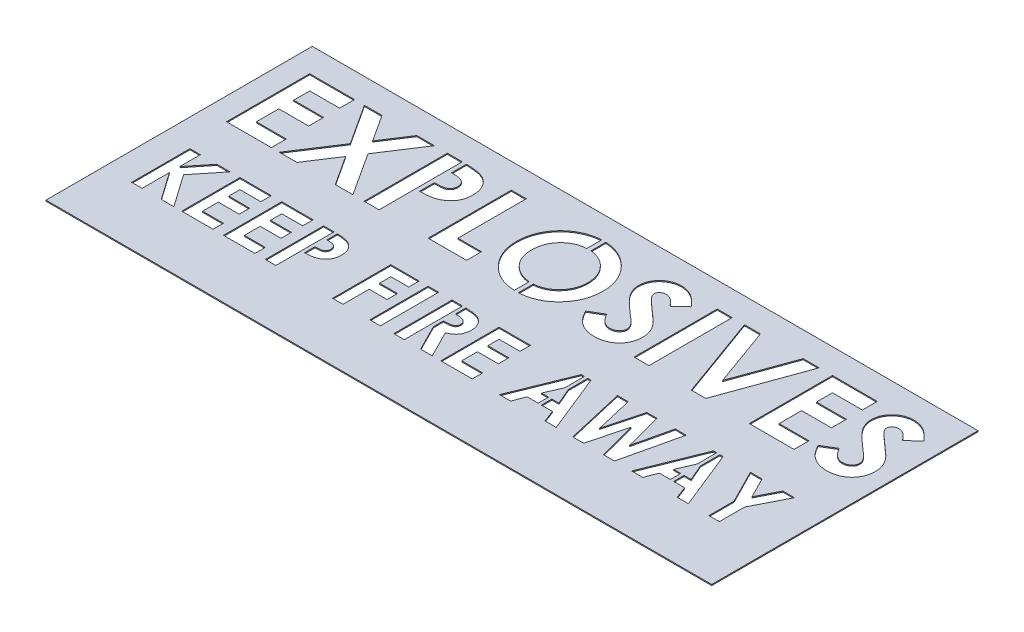
SolidWorks part; units mm, degrees
ref_plane "Front Plane" through (0, 0, 0) normal (0, 0, 1) x (1, 0, 0)
ref_plane "Top Plane" through (0, 0, 0) normal (0, 1, 0) x (1, 0, 0)
ref_plane "Right Plane" through (0, 0, 0) normal (1, 0, 0) x (0, 0, -1)
sketch "Sketch1" plane through (0, 0, 0) normal (0, 1, 0) x (1, 0, 0)
  line L1 (127, -50.8) -> (-127, -50.8)
  line L2 (127, -50.8) -> (127, 50.8)
  line L3 (127, 50.8) -> (-127, 50.8)
  line L4 (-127, -50.8) -> (-127, 50.8)
  line L5 (127, -50.8) -> (-127, 50.8) construction
  line L6 (127, 50.8) -> (-127, -50.8) construction
  point P0 (0, 0)
  dimension "D1" = 254
  dimension "D2" = 101.6
extrude "Boss-Extrude1" add sketch "Sketch1" along normal blind 0.4
sketch "Sketch2" plane through (0, 0.4, 0) normal (0, 1, 0) x (1, 0, 0)
  line L0 (-127, 9.525) -> (127, 9.525) construction
  line L1 (-127, 50.8) -> (-127, -50.8) construction
  line L2 (127, -50.8) -> (127, 50.8) construction
  line L3 (0, 0) -> (127, 0) construction
  line L4 (-127, -28.575) -> (127, -28.575) construction
  text T0 "<b>EXPLOSIVES</b>" font "Century Gothic" height 31.75
  text T1 "<b>KEEP FIRE AWAY</b>" font "Century Gothic" height 22.225
  dimension "D1" = 9.525
  dimension "D2" = 28.575
extrude "Cut-Extrude1" cut sketch "Sketch2" against normal through all
sketch "Sketch3" plane through (0, 0.4, 0) normal (0, 1, 0) x (1, 0, 0)
  line L0 (-65.9423, 41.275) -> (-59.5821, 41.275) construction
  line L1 (34.6175, -24.016) -> (33.9825, -24.016) construction
  line L2 (-60.2436, 41.275) -> (-59.5821, 41.275) construction
  line L3 (-60.2436, 23.3647) -> (-60.2436, 41.275)
  line L4 (-58.6561, 41.2679) -> (-58.6561, 23.38)
  line L5 (-7.1488, 36.3904) -> (-7.0598, 42.0891) construction
  line L6 (-7.854, 42.0721) -> (-7.854, 8.7339)
  line L7 (-6.2665, 8.7336) -> (-6.2665, 42.0473)
  line L8 (-6.2665, 42.0473) -> (-6.2665, 42.0649)
  line L9 (-65.5353, -6.35) -> (-61.0831, -6.35) construction
  line L10 (-61.5462, -6.35) -> (-61.0831, -6.35) construction
  line L11 (-61.5462, -18.8872) -> (-61.5462, -6.35)
  line L12 (-60.2762, -6.3576) -> (-60.2762, -18.8724)
  line L13 (-12.5372, -18.8872) -> (-12.5372, -6.35)
  line L14 (-16.5263, -6.35) -> (-11.8783, -6.35) construction
  line L15 (33.9825, -6.35) -> (35.2525, -6.35) construction
  line L16 (-11.1837, -18.8872) -> (-12.5372, -18.8872) construction
  line L17 (39.4592, -24.016) -> (29.7847, -24.016) construction
  line L18 (-12.5372, -6.35) -> (-11.8783, -6.35) construction
  line L19 (-11.2672, -18.8872) -> (-12.5372, -18.8872) construction
  line L20 (-11.2672, -6.3538) -> (-11.2672, -18.8872)
  line L21 (32.7632, -6.35) -> (36.4718, -6.35) construction
  line L22 (35.2525, -24.016) -> (34.6175, -24.016) construction
  line L23 (32.7632, -6.35) -> (36.4718, -6.35) construction
  line L24 (34.6175, -24.016) -> (34.6175, -6.35) construction
  line L25 (33.9825, -6.35) -> (33.9825, -24.016)
  line L26 (35.2525, -24.016) -> (35.2525, -6.35)
  line L27 (83.1968, -6.35) -> (86.9054, -6.35) construction
  line L28 (89.8928, -24.016) -> (80.2184, -24.016) construction
  line L29 (83.1968, -6.35) -> (86.9054, -6.35) construction
  line L30 (89.8928, -24.016) -> (80.2184, -24.016) construction
  line L31 (85.0556, -24.016) -> (85.0511, -6.35) construction
  line L32 (84.4206, -6.35) -> (84.4206, -24.016)
  line L33 (85.6906, -24.0157) -> (85.6906, -6.35)
  line L34 (84.4206, -24.016) -> (85.6906, -24.0157) construction
  line L35 (85.6906, -6.35) -> (84.4206, -6.35) construction
  line L36 (-60.2436, 23.3647) -> (-60.2436, 21.4896)
  line L37 (-60.2436, 23.3647) -> (-60.2436, 9.525) construction
  line L38 (-60.2436, 21.4896) -> (-58.6561, 21.4896)
  line L39 (-58.6561, 21.4896) -> (-58.6561, 23.38)
  line L40 (-60.2436, 41.275) -> (-60.2436, 42.7723)
  line L41 (-60.2436, 42.7723) -> (-58.6561, 42.7723)
  line L42 (-58.6561, 42.7723) -> (-58.6561, 41.2679)
  line L43 (-6.2665, 42.0473) -> (-6.2665, 43.225)
  line L44 (-6.2665, 43.225) -> (-7.854, 43.225)
  line L45 (-7.854, 43.225) -> (-7.854, 42.0721)
  line L46 (-6.2665, 8.7336) -> (-6.2665, 7.0601)
  line L47 (-6.2665, 7.0601) -> (-7.854, 7.0601)
  line L48 (-7.854, 7.0601) -> (-7.854, 8.7339)
  line L49 (-60.2762, -6.3576) -> (-60.2762, -5.1927)
  line L50 (-60.2762, -5.1927) -> (-61.5462, -5.1927)
  line L51 (-61.5462, -5.1927) -> (-61.5462, -6.35)
  line L52 (-60.2762, -18.8724) -> (-60.2762, -20.3856)
  line L53 (-60.2762, -20.3856) -> (-61.5462, -20.3856)
  line L54 (-61.5462, -18.8872) -> (-61.5462, -28.575) construction
  line L55 (-61.5462, -20.3856) -> (-61.5462, -18.8872)
  line L56 (-11.2672, -6.3538) -> (-11.2672, -5.3156)
  line L57 (-11.2672, -5.3156) -> (-12.5372, -5.3156)
  line L58 (-12.5372, -5.3156) -> (-12.5372, -6.35)
  line L59 (-11.2672, -18.8872) -> (-11.2672, -21.0537)
  line L60 (-11.2672, -21.0537) -> (-12.5372, -21.0537)
  line L61 (-12.5372, -18.8872) -> (-12.5372, -28.575) construction
  line L62 (-12.5372, -21.0537) -> (-12.5372, -18.8872)
  line L63 (35.2525, -6.35) -> (35.2525, -5.3156)
  line L64 (35.2525, -5.3156) -> (33.9825, -5.3156)
  line L65 (33.9825, -5.3156) -> (33.9825, -6.35)
  line L66 (35.2525, -24.016) -> (35.2525, -24.9696)
  line L67 (35.2525, -24.9696) -> (33.9825, -24.9696)
  line L68 (33.9825, -24.9696) -> (33.9825, -24.016)
  line L69 (85.6906, -6.35) -> (85.6906, -5.3156)
  line L70 (85.6906, -5.3156) -> (84.4206, -5.3156)
  line L71 (84.4206, -5.3156) -> (84.4206, -6.35)
  line L72 (85.6906, -24.0157) -> (85.6906, -25.9909)
  line L73 (85.6906, -25.9909) -> (84.4206, -25.9909)
  line L74 (84.4206, -25.9909) -> (84.4206, -24.016)
  spline S0 degree 3 poles (383.5394, -1927.5608) (-38.8451, 59.062) (-43.4399, 25.3763) (-54.8741, 23.6308) (-55.5465, 23.5489) (-56.3099, 23.4786) (-57.1649, 23.4307) (-58.1106, 23.3934) (-87.054, 22.6351) (-116.0138, 50.1547) (-120.4882, -1975.0593) knots -5.060584 -5.060584 -5.060584 -5.060584 0.077373 0.167614 0.272108 0.390016 0.521363 0.667272 0.82681 13.882944 13.882944 13.882944 13.882944 only from (-53.7753, 23.8481) to (-60.2436, 23.3647) construction
  spline S1 degree 3 poles (-112.4571, 2039.966) (-113.971, 10.9667) (-85.535, 42.2922) (-57.2087, 41.226) (-56.1421, 41.148) (-55.1653, 41.0517) (-54.2787, 40.9166) (-53.4812, 40.7617) (-52.7726, 40.5729) (-52.1449, 40.3489) (-51.5815, 40.0848) (-51.0484, 39.8036) (-50.5576, 39.4679) (-50.0843, 39.114) (-49.6556, 38.708) (-49.2447, 38.277) (-48.869, 37.8038) (-48.5269, 37.2943) (-48.2165, 36.7578) (-47.9453, 36.1934) (-47.7253, 35.6001) (-47.5407, 34.9818) (-47.3925, 34.3386) (-47.2939, 33.6664) (-45.8884, 19.0605) (-81.1777, 2.9062) (1951.7962, 86.9694) knots -4.62995 -4.62995 -4.62995 -4.62995 0.070781 0.136552 0.197012 0.252923 0.303687 0.349719 0.39124 0.428479 0.463057 0.49715 0.531002 0.564226 0.597701 0.631421 0.665597 0.700451 0.735881 0.771092 0.806975 0.843534 0.88094 0.919294 0.95918 3.378005 3.378005 3.378005 3.378005 only from (-59.5821, 41.275) to (-47.2179, 32.2563) construction
  spline S2 degree 3 poles (-58.6561, 23.38) (-58.81, 23.3763) (-59.3391, 23.366) (-59.8683, 23.3652) (-60.2436, 23.3647) knots 0.75576 0.75576 0.75576 0.75576 0.82681 1 1 1 1 construction
  spline S3 degree 3 poles (-59.5821, 41.275) (-59.2734, 41.2736) (-58.9647, 41.2722) (-58.6561, 41.2679) knots 0 0 0 0 0.052578 0.052578 0.052578 0.052578 construction
  spline S4 degree 3 poles (-90.3304, -1989.1071) (40.631, 60.3711) (13.1894, 5.52) (-10.4257, 8.9974) (-12.0345, 9.3699) (-13.5593, 9.9257) (-15.0158, 10.6206) (-16.3933, 11.4764) (-17.6912, 12.4917) (-18.9022, 13.6405) (-19.9993, 14.8976) (-20.9677, 16.2255) (-21.7846, 17.6142) (-22.4499, 19.0643) (-22.9745, 20.5669) (-23.3445, 22.131) (-26.5892, 46.207) (24.4447, 73.3551) (-2022.084, -39.3514) knots -2.530865 -2.530865 -2.530865 -2.530865 0.066749 0.131152 0.193732 0.255326 0.316388 0.378027 0.440406 0.504557 0.568658 0.630986 0.692288 0.752615 0.8132 0.874016 0.936158 3.586141 3.586141 3.586141 3.586141 only from (-7.0153, 8.7109) to (-23.609, 25.4127) construction
  spline S5 degree 3 poles (2007.8991, -39.1213) (-39.7016, 73.2922) (12.3981, 46.0644) (9.0921, 21.9673) (8.7146, 20.3876) (8.1946, 18.872) (7.5127, 17.4278) (6.6911, 16.0459) (5.7081, 14.739) (4.5996, 13.5079) (3.3792, 12.3904) (2.0866, 11.4056) (0.7278, 10.5711) (-0.6952, 9.8873) (-2.1856, 9.3567) (-3.7395, 8.9823) (-27.3121, 5.6661) (-54.205, 57.9292) (64.9599, -1989.5489) knots -2.612661 -2.612661 -2.612661 -2.612661 0.065722 0.129508 0.191722 0.253161 0.314316 0.375952 0.43862 0.502973 0.567129 0.629552 0.690477 0.751072 0.811668 0.872929 0.935501 3.55637 3.55637 3.55637 3.55637 only from (9.3622, 25.3046) to (-7.0153, 8.7109) construction
  spline S6 degree 3 poles (71.0097, 2040.0874) (-53.3082, -7.8893) (-26.8068, 45.1856) (-3.8153, 41.8114) (-2.2708, 41.4281) (-0.7852, 40.8954) (0.6378, 40.1988) (2.0032, 39.3579) (3.306, 38.3571) (4.5331, 37.2195) (5.6671, 35.9825) (6.6497, 34.6506) (7.4877, 33.2584) (8.1821, 31.8021) (8.7111, 30.2716) (9.0823, 28.6748) (12.4857, 4.9459) (-41.1897, -22.3301) (2007.4548, 101.6982) knots -2.477585 -2.477585 -2.477585 -2.477585 0.063396 0.125157 0.185649 0.245977 0.306108 0.367351 0.429902 0.49454 0.559373 0.62241 0.684357 0.745807 0.80743 0.869996 0.933928 3.555613 3.555613 3.555613 3.555613 only from (-7.0598, 42.0891) to (9.3622, 25.3046) construction
  spline S7 degree 3 poles (-2022.6948, 76.2047) (16.9362, -12.9796) (-25.5032, 8.3237) (-23.4786, 27.6407) (-23.3117, 28.7252) (-23.0649, 29.7837) (-22.765, 30.8238) (-22.3765, 31.8358) (-21.9343, 32.8305) (-21.4177, 33.7961) (-20.8432, 34.7238) (-20.2163, 35.6091) (-19.5356, 36.4414) (-18.8032, 37.2261) (-18.0165, 37.9582) (-17.1859, 38.6478) (-16.2954, 39.2768) (-15.3643, 39.8605) (-14.398, 40.3883) (-13.4004, 40.8376) (-12.3919, 41.2299) (-11.3593, 41.5396) (-10.3135, 41.7918) (-9.2433, 41.9585) (9.6876, 43.9814) (30.6648, 1.6667) (-61.6622, 2041.0656) knots -2.100804 -2.100804 -2.100804 -2.100804 0.043114 0.085683 0.127594 0.169059 0.210432 0.251811 0.293444 0.335381 0.377477 0.418688 0.459873 0.500873 0.541873 0.583212 0.624763 0.666988 0.70937 0.751103 0.792568 0.833545 0.874827 0.916018 0.957859 3.05911 3.05911 3.05911 3.05911 only from (-23.609, 25.4127) to (-7.0598, 42.0891) construction
  spline S8 degree 3 poles (-7.0153, 8.7109) (-7.295, 8.7172) (-7.5746, 8.7236) (-7.854, 8.7339) knots 0 0 0 0 0.03197 0.03197 0.03197 0.03197 construction
  spline S9 degree 3 poles (-6.2665, 8.7336) (-6.516, 8.7241) (-6.7656, 8.7175) (-7.0153, 8.7109) knots 0.971159 0.971159 0.971159 0.971159 1 1 1 1 construction
  spline S10 degree 3 poles (-7.0598, 42.0891) (-6.7953, 42.0823) (-6.5308, 42.0754) (-6.2665, 42.0649) knots 0 0 0 0 0.030378 0.030378 0.030378 0.030378 construction
  spline S11 degree 3 poles (-7.854, 42.0721) (-7.5895, 42.082) (-7.3246, 42.0856) (-7.0598, 42.0891) knots 0.969595 0.969595 0.969595 0.969595 1 1 1 1 construction
  spline S12 degree 3 poles (373.5191, -1971.5508) (-45.8503, 12.1972) (-48.8248, -17.3327) (-57.7875, -18.7009) (-58.2582, -18.7582) (-58.7926, -18.8075) (-59.3911, -18.841) (-60.053, -18.8671) (-82.7824, -19.4626) (-105.584, 4.9129) (-104.0677, -2018.0259) knots -5.699386 -5.699386 -5.699386 -5.699386 0.077373 0.167614 0.272108 0.390016 0.521363 0.667272 0.82681 15.511175 15.511175 15.511175 15.511175 only from (-57.0183, -18.5488) to (-61.5462, -18.8872) construction
  spline S13 degree 3 poles (-96.6977, 1992.9451) (-104.0472, -33.2908) (-81.6537, -5.5475) (-59.4217, -6.3843) (-58.6751, -6.4389) (-57.9914, -6.5063) (-57.3707, -6.6009) (-56.8125, -6.7093) (-56.3164, -6.8414) (-55.877, -6.9982) (-55.4827, -7.1831) (-55.1095, -7.38) (-54.766, -7.615) (-54.4347, -7.8627) (-54.1346, -8.1469) (-53.8469, -8.4486) (-53.584, -8.7798) (-53.3444, -9.1365) (-53.1272, -9.512) (-52.9373, -9.9071) (-52.7833, -10.3224) (-52.6542, -10.7552) (-52.5504, -11.2055) (-52.4813, -11.676) (-51.3792, -23.1291) (-82.6139, -35.9876) (1946.3364, 50.9106) knots -5.215064 -5.215064 -5.215064 -5.215064 0.070781 0.136552 0.197012 0.252923 0.303687 0.349719 0.39124 0.428479 0.463057 0.49715 0.531002 0.564226 0.597701 0.631421 0.665597 0.700451 0.735881 0.771092 0.806975 0.843534 0.88094 0.919294 0.95918 3.678161 3.678161 3.678161 3.678161 only from (-61.0831, -6.35) to (-52.4282, -12.6631) construction
  spline S14 degree 3 poles (-60.2762, -18.8724) (-60.4368, -18.8769) (-60.8601, -18.8863) (-61.2835, -18.8868) (-61.5462, -18.8872) knots 0.72086 0.72086 0.72086 0.72086 0.82681 1 1 1 1 construction
  spline S15 degree 3 poles (-61.0831, -6.35) (-60.8141, -6.3512) (-60.5451, -6.3524) (-60.2762, -6.3576) knots 0 0 0 0 0.065456 0.065456 0.065456 0.065456 construction
  spline S16 degree 3 poles (-38.8225, 1993.0808) (-55.6175, -34.4332) (-32.7181, -5.509) (-10.1281, -6.3863) (-9.3454, -6.4323) (-8.6308, -6.5026) (-7.9848, -6.5958) (-7.4065, -6.7056) (-6.8961, -6.8308) (-6.4492, -6.9868) (-6.0459, -7.1627) (-5.67, -7.3649) (-5.3132, -7.591) (-4.9778, -7.847) (-4.6609, -8.1284) (-4.362, -8.4354) (-4.0853, -8.7705) (-3.8325, -9.1317) (-3.602, -9.5118) (-3.3984, -9.9111) (-3.2327, -10.3299) (-3.0864, -10.7623) (-2.981, -11.2144) (-2.9077, -11.6819) (-1.7182, -22.4157) (-35.2021, -34.8541) (1995.5236, 63.7548) knots -5.160685 -5.160685 -5.160685 -5.160685 0.072889 0.140186 0.202277 0.258895 0.310483 0.357095 0.398514 0.435038 0.469251 0.502805 0.53621 0.569379 0.602801 0.636666 0.670929 0.705803 0.741189 0.776304 0.812004 0.847969 0.884522 0.921974 0.960198 3.443654 3.443654 3.443654 3.443654 only from (-11.8783, -6.35) to (-2.8494, -12.6631) construction
  spline S17 degree 3 poles (-11.8783, -6.35) (-11.6746, -6.3507) (-11.4709, -6.3514) (-11.2672, -6.3538) knots 0 0 0 0 0.048328 0.048328 0.048328 0.048328 construction
  dimension "D1" = 1.5875
  dimension "D2" = 1.5875
  dimension "D3" = 1.27
  dimension "D4" = 1.27
  dimension "D5" = 1.27
  dimension "D6" = 1.27
extrude "Boss-Extrude6" add sketch "Sketch3" against normal up to surface (0.4 mm away) contours L42 L41 L40 L3 L36 L38 L39 L4 | L48 L47 L46 L7 L8 L43 L44 L45 L6 | L55 L53 L52 L12 L49 L50 L51 L11 | L62 L60 L59 L20 L56 L57 L58 L13 | L74 L73 L72 L33 L69 L70 L71 L32 | L25 L68 L67 L66 L26 L63 L64 L65 up to face at (-90.1347, 0, 17.1776)
